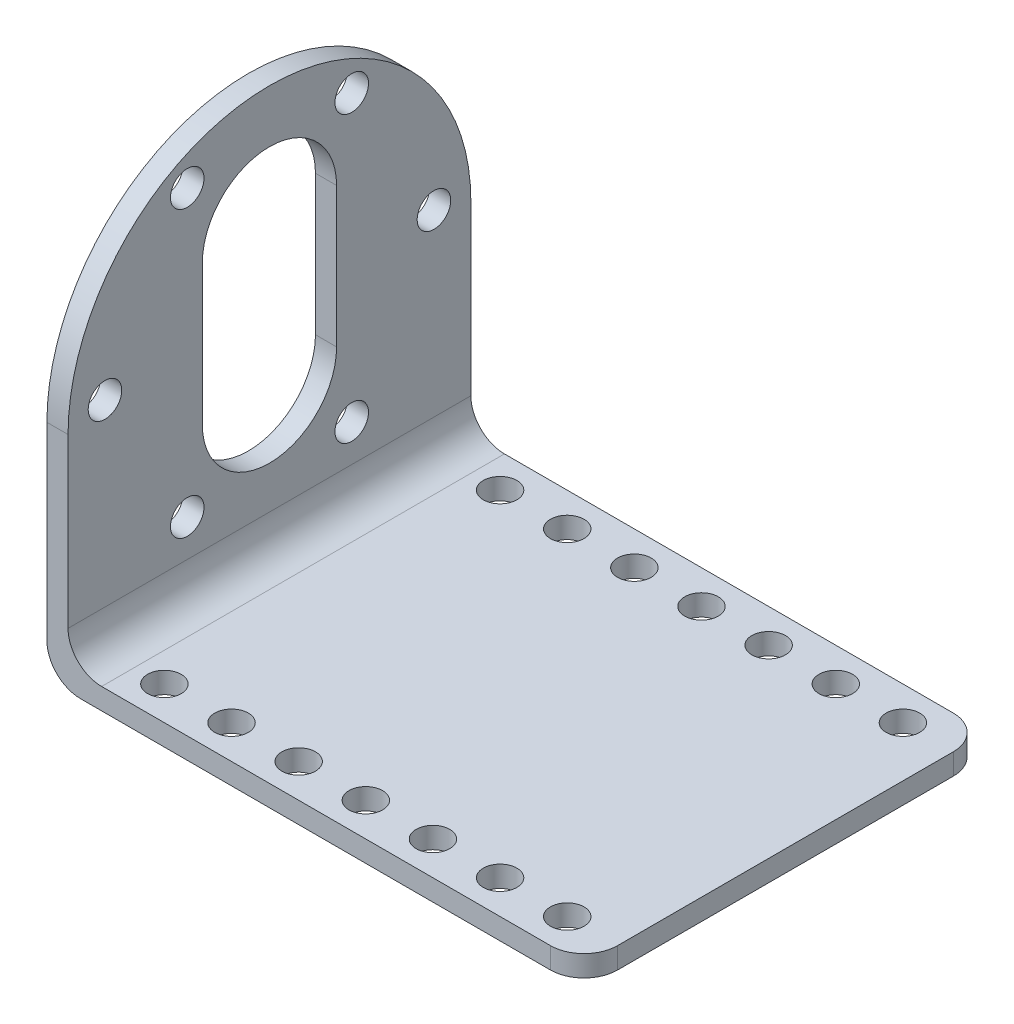
SolidWorks part; units mm, degrees
ref_plane "Front Plane" through (0, 0, 0) normal (0, 0, 1) x (1, 0, 0)
ref_plane "Top Plane" through (0, 0, 0) normal (0, 1, 0) x (1, 0, 0)
ref_plane "Right Plane" through (0, 0, 0) normal (1, 0, 0) x (0, 0, -1)
sketch "Sketch1" plane through (0, 0, 0) normal (0, 1, 0) x (1, 0, 0)
  line L1 (-46.8817, 7.3767) -> (3.9183, 7.3767)
  line L2 (-46.8817, 7.3767) -> (-46.8817, -30.7233)
  line L3 (-46.8817, -30.7233) -> (3.9183, -30.7233)
  line L4 (3.9183, 7.3767) -> (3.9183, -30.7233)
  dimension "D1" = 50.8
  dimension "D2" = 38.1
extrude "Boss-Extrude1" add sketch "Sketch1" along normal blind 2
ref_plane "Plane1" through (0, 2, 0) normal (0, 1, 0) x (1, 0, 0)
sketch "Sketch2" plane through (0, 2, 0) normal (0, 1, 0) x (1, 0, 0)
  line L0 (-46.8817, -30.7233) -> (3.9183, -30.7233) construction
  line L1 (-46.8817, 7.3767) -> (-44.8817, 7.3767)
  line L2 (-46.8817, 7.3767) -> (-46.8817, -30.7233)
  line L3 (-46.8817, -30.7233) -> (-44.8817, -30.7233)
  line L4 (-44.8817, 7.3767) -> (-44.8817, -30.7233)
  dimension "D1" = 2
extrude "Boss-Extrude2" add sketch "Sketch2" along normal blind 38.1
ref_plane "Plane2" through (-46.8817, 0, 30.7233) normal (1, 0, 0) x (0, 0, -1)
sketch "Sketch4" plane through (0, 2, 0) normal (0, 1, 0) x (1, 0, 0)
  line L0 (3.9183, -30.7233) -> (-0.8442, -30.7233)
  line L1 (-44.8817, -30.7233) -> (3.9183, -30.7233) construction
  line L2 (-0.8442, -30.7233) -> (-0.8442, -27.5483)
  line L3 (-0.8442, -27.5483) -> (-7.1942, -27.5483)
  line L4 (-4.0192, -27.5483) -> (-4.0192, -29.8768)
  line L5 (-4.0192, -29.8768) -> (-4.0192, -25.485)
  circle A0 centre (-0.8442, -27.5483) radius 1.5875
  circle A1 centre (-7.1942, -27.5483) radius 1.5875
  circle A2 centre (-7.1942, -27.5483) radius 1.5875
  circle A3 centre (-13.5442, -27.5483) radius 1.5875
  circle A4 centre (-19.8942, -27.5483) radius 1.5875
  circle A5 centre (-26.2442, -27.5483) radius 1.5875
  circle A6 centre (-32.5942, -27.5483) radius 1.5875
  circle A7 centre (-38.9442, -27.5483) radius 1.5875
  circle A8 centre (-0.8442, 4.2017) radius 1.5875
  circle A9 centre (-7.1942, 4.2017) radius 1.5875
  circle A10 centre (-13.5442, 4.2017) radius 1.5875
  circle A11 centre (-19.8942, 4.2017) radius 1.5875
  circle A12 centre (-26.2442, 4.2017) radius 1.5875
  circle A13 centre (-32.5942, 4.2017) radius 1.5875
  circle A14 centre (-38.9442, 4.2017) radius 1.5875
  dimension "D3" = 3.175
  dimension "D1" = 4.7625
  dimension "D2" = 3.175
  dimension "D4" = 6.35
  dimension "D5" = 7
  dimension "D6" = 2
  dimension "D7" = 7
extrude "Cut-Extrude1" cut sketch "Sketch4" against normal blind 5.08
sketch "Sketch5" plane through (-46.8817, 0, 30.7233) normal (1, 0, 0) x (0, 0, -1)
  line L0 (19.05, 21.05) -> (38.1, 21.05)
  line L1 (38.1, 21.05) -> (0, 21.05)
  line L4 (0, 40.1) -> (38.1, 40.1)
  line L5 (0, 40.1) -> (0, 21.05)
  line L6 (0, 21.05) -> (38.1, 21.05)
  line L7 (38.1, 40.1) -> (38.1, 21.05)
  arc A0 (38.1, 21.05) -> (0, 21.05) centre (19.05, 21.05) ccw
extrude "Cut-Extrude3" cut sketch "Sketch5" along normal blind 2.54 contours A0 L7 L4 | A0 L4 L5
fillet "Fillet1" radius 3.175 4 edges at (-46.8817, 0, 11.6733) (3.9183, 1, -7.3767) (3.9183, 1, 30.7233)
sketch "Sketch6" plane through (-46.8817, 0, 30.7233) normal (1, 0, 0) x (0, 0, -1)
  line L2 (0, 3.175) -> (19.05, 3.175)
  line L3 (38.1, 3.175) -> (0, 3.175) construction
  line L10 (25.4, 21.05) -> (25.4, 28.75)
  line L11 (25.4, 21.05) -> (25.4, 15.525)
  line L13 (12.7, 21.05) -> (12.7, 15.525)
  line L14 (12.7, 21.05) -> (12.7, 28.75)
  arc A0 (38.1, 21.05) -> (0, 21.05) centre (19.05, 21.05) ccw construction
  arc A1 (25.4, 28.75) -> (12.7, 28.75) centre (19.05, 28.75) ccw
  arc A2 (12.7, 15.525) -> (25.4, 15.525) centre (19.05, 15.525) ccw
  circle A3 centre (34.6075, 22.1375) radius 1.5875
  circle A4 centre (26.8287, 8.6643) radius 1.5875
  circle A5 centre (11.2712, 8.6643) radius 1.5875
  circle A6 centre (3.4925, 22.1375) radius 1.5875
  circle A7 centre (11.2713, 35.6107) radius 1.5875
  circle A8 centre (26.8288, 35.6107) radius 1.5875
  point P0 (19.05, 40.1)
  point P33 (19.05, 22.1375)
  dimension "D1" = 6
extrude "Cut-Extrude4" cut sketch "Sketch6" along normal blind 2.54 contours A8 | A7 | A6 | L13 A2 L11 L10 A1 L14 | A3 | A4 | A5
